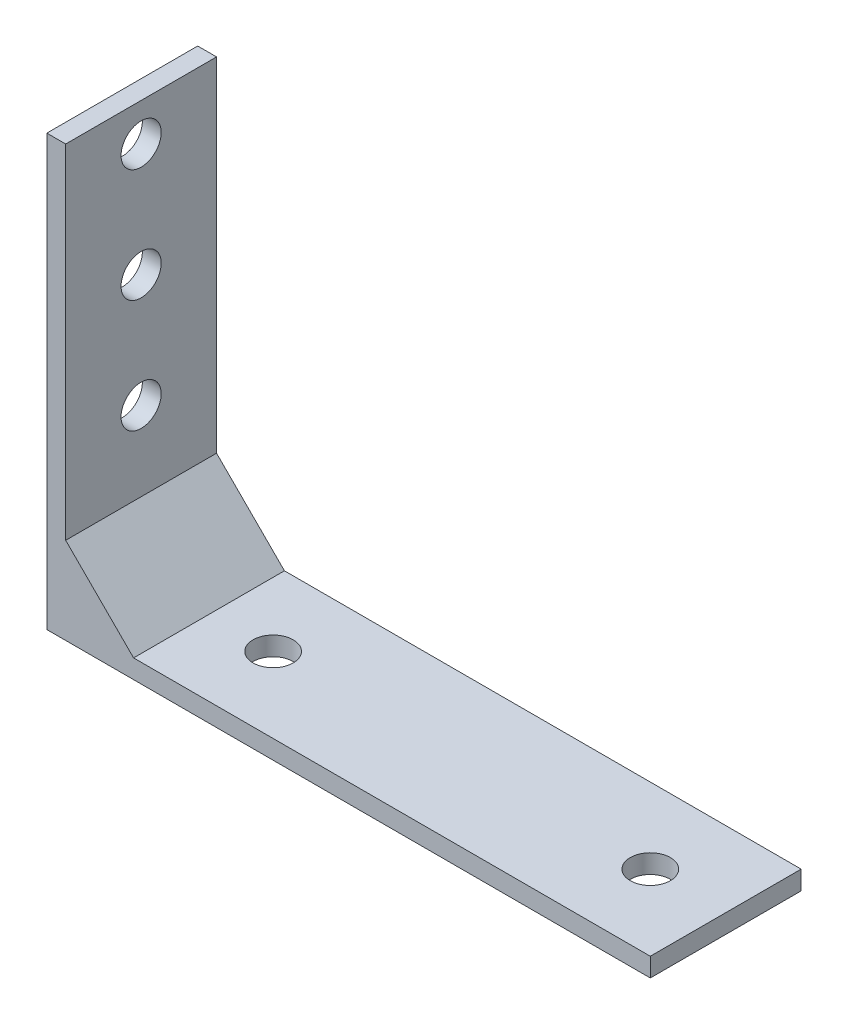
SolidWorks part; units mm, degrees
ref_plane "Front Plane" through (0, 0, 0) normal (0, 0, 1) x (1, 0, 0)
ref_plane "Top Plane" through (0, 0, 0) normal (0, 1, 0) x (1, 0, 0)
ref_plane "Right Plane" through (0, 0, 0) normal (1, 0, 0) x (0, 0, -1)
sketch "Sketch1" plane through (0, 0, 0) normal (0, 0, 1) x (1, 0, 0)
  line L1 (0, 0) -> (3.175, 0)
  line L2 (0, 0) -> (0, 72.39)
  line L3 (0, 72.39) -> (3.175, 72.39)
  line L4 (3.175, 3.175) -> (3.175, 72.39)
  line L5 (0, 0) -> (101.6, 0)
  line L6 (0, 0) -> (0, 3.175)
  line L7 (3.175, 3.175) -> (101.6, 3.175)
  line L8 (101.6, 0) -> (101.6, 3.175)
  dimension "D1" = 101.6
  dimension "D2" = 3.175
  dimension "D3" = 3.175
  dimension "D4" = 72.39
extrude "Boss-Extrude1" add sketch "Sketch1" along normal blind 25.4 contours L5 L8 L7 L4 L3 L2 L1
sketch "Sketch2" plane through (0, 3.175, 0) normal (0, 1, 0) x (1, 0, 0)
  line L0 (101.6, -25.4) -> (101.6, 0) construction
  line L1 (3.175, -25.4) -> (101.6, -25.4) construction
  circle A0 centre (88.9, -12.7) radius 3.3782
  circle A1 centre (25.4, -12.7) radius 3.3782
  dimension "D5" = 6.7564
  dimension "D6" = 6.7564
  dimension "D2" = 63.5
  dimension "D1" = 12.7
  dimension "D3" = 12.7
  dimension "D4" = 12.7
extrude "Cut-Extrude1" cut sketch "Sketch2" against normal blind 25.4
sketch "Sketch3" plane through (0, 0, 0) normal (-1, 0, 0) x (0, 0, 1)
  line L0 (25.4, 0) -> (0, 0) construction
  line L2 (0, 3.175) -> (0, 72.39) construction
  circle A0 centre (12.7, 27.94) radius 3.3782
  circle A1 centre (12.7, 46.99) radius 3.3782
  circle A2 centre (12.7, 66.04) radius 3.3782
  dimension "D1" = 6.7564
  dimension "D2" = 6.7564
  dimension "D3" = 6.7564
  dimension "D4" = 27.94
  dimension "D5" = 19.05
  dimension "D6" = 19.05
  dimension "D7" = 12.7
  dimension "D8" = 12.7
  dimension "D9" = 12.7
extrude "Cut-Extrude2" cut sketch "Sketch3" against normal through all
sketch "Sketch4" plane through (0, 0, 25.4) normal (0, 0, 1) x (1, 0, 0)
  line L0 (3.175, 14.605) -> (14.605, 3.175)
  line L1 (3.175, 3.175) -> (3.175, 72.39) construction
  line L2 (3.175, 3.175) -> (101.6, 3.175) construction
  line L3 (14.605, 3.175) -> (3.175, 3.175)
  line L4 (3.175, 3.175) -> (3.175, 14.605)
  dimension "D1" = 45
  dimension "D2" = 11.43
extrude "Boss-Extrude2" add sketch "Sketch4" against normal blind 25.4
